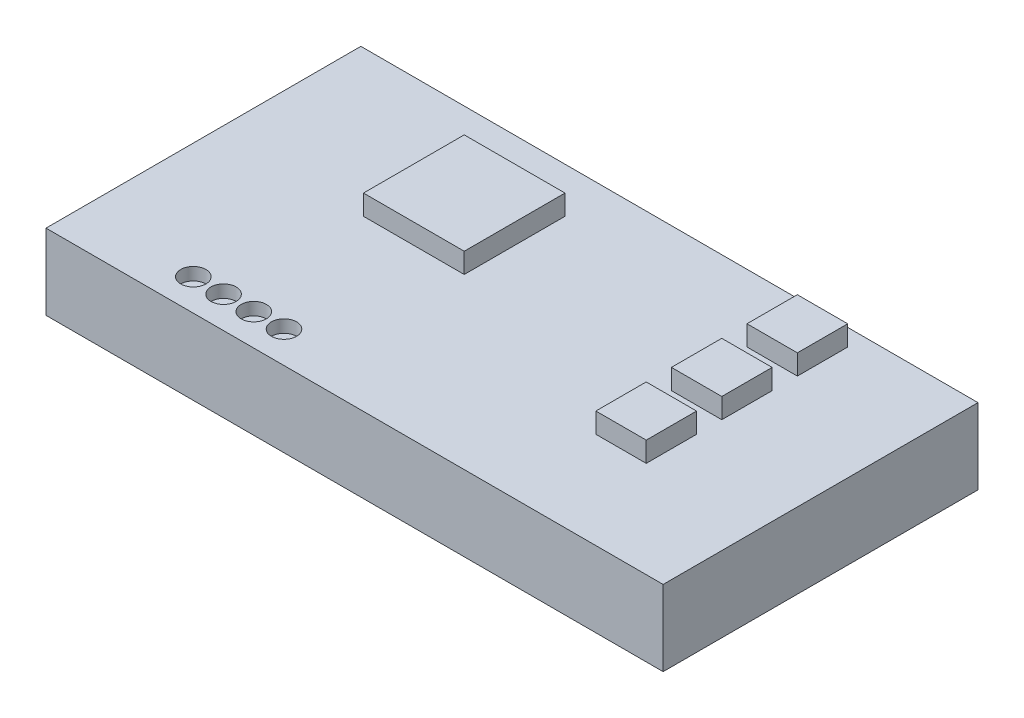
SolidWorks part; units mm, degrees
ref_plane "Alzado" through (0, 0, 0) normal (0, 0, 1) x (1, 0, 0)
ref_plane "Planta" through (0, 0, 0) normal (0, 1, 0) x (1, 0, 0)
ref_plane "Vista lateral" through (0, 0, 0) normal (1, 0, 0) x (0, 0, -1)
sketch "Croquis1" plane through (0, 0, 0) normal (0, 1, 0) x (1, 0, 0)
  line L1 (-12.25, 6.25) -> (12.25, 6.25)
  line L2 (-12.25, 6.25) -> (-12.25, -6.25)
  line L3 (-12.25, -6.25) -> (12.25, -6.25)
  line L4 (12.25, 6.25) -> (12.25, -6.25)
  line L5 (-12.25, 6.25) -> (12.25, -6.25) construction
  line L6 (-12.25, -6.25) -> (12.25, 6.25) construction
  point P0 (0, 0)
  dimension "D1" = 24.5
  dimension "D2" = 12.5
extrude "Saliente-Extruir1" add sketch "Croquis1" along normal blind 3
sketch "Croquis2" plane through (0, 3, 0) normal (0, 1, 0) x (1, 0, 0)
  line L0 (-12.25, -6.25) -> (12.25, -6.25) construction
  circle A0 centre (-7.6549, -4.9963) radius 0.5
  circle A1 centre (-6.4549, -4.9963) radius 0.5
  circle A2 centre (-5.2549, -4.9963) radius 0.5
  circle A3 centre (-4.0549, -4.9963) radius 0.5
  dimension "D1" = 1
  dimension "D2" = 7.6549
  dimension "D3" = 1.2537
  dimension "D5" = 1.2
  dimension "D4" = 4
extrude "Cortar-Extruir1" cut sketch "Croquis2" against normal blind 0.5
sketch "Croquis3" plane through (0, 3, 0) normal (0, 1, 0) x (1, 0, 0)
  line L0 (5.7525, 2.5746) -> (7.7525, 2.5746)
  line L1 (-6.3538, 4.4576) -> (-2.3538, 4.4576)
  line L2 (-6.3538, 4.4576) -> (-6.3538, 0.4576)
  line L3 (-6.3538, 0.4576) -> (-2.3538, 0.4576)
  line L4 (-2.3538, 4.4576) -> (-2.3538, 0.4576)
  line L5 (-6.3538, 4.4576) -> (-2.3538, 0.4576) construction
  line L6 (-6.3538, 0.4576) -> (-2.3538, 4.4576) construction
  line L7 (5.7525, 5.5746) -> (7.7525, 5.5746)
  line L8 (5.7525, 5.5746) -> (5.7525, 3.5765)
  line L9 (5.7525, 3.5765) -> (7.7525, 3.5765)
  line L10 (7.7525, 5.5746) -> (7.7525, 3.5765)
  line L11 (5.7525, 5.5746) -> (7.7525, 3.5765) construction
  line L12 (5.7525, 3.5765) -> (7.7525, 5.5746) construction
  line L13 (5.7525, 2.5746) -> (5.7525, 0.5765)
  line L14 (5.7525, 0.5765) -> (7.7525, 0.5765)
  line L15 (7.7525, 2.5746) -> (7.7525, 0.5765)
  line L16 (5.7525, 2.5746) -> (7.7525, 0.5765) construction
  line L17 (5.7525, 0.5765) -> (7.7525, 2.5746) construction
  line L18 (5.7525, -0.4254) -> (7.7525, -0.4254)
  line L19 (5.7525, -0.4254) -> (5.7525, -2.4235)
  line L20 (5.7525, -2.4235) -> (7.7525, -2.4235)
  line L21 (7.7525, -0.4254) -> (7.7525, -2.4235)
  line L22 (5.7525, -0.4254) -> (7.7525, -2.4235) construction
  line L23 (5.7525, -2.4235) -> (7.7525, -0.4254) construction
  point P0 (-4.3538, 2.4576)
  point P5 (6.7525, 4.5756)
  point P12 (6.7525, 1.5756)
  point P17 (6.7525, -1.4244)
  dimension "D1" = 4
  dimension "D2" = 1.9981
  dimension "D3" = 2
  dimension "D4" = 4
  dimension "D5" = 3
extrude "Saliente-Extruir2" add sketch "Croquis3" along normal blind 0.8
